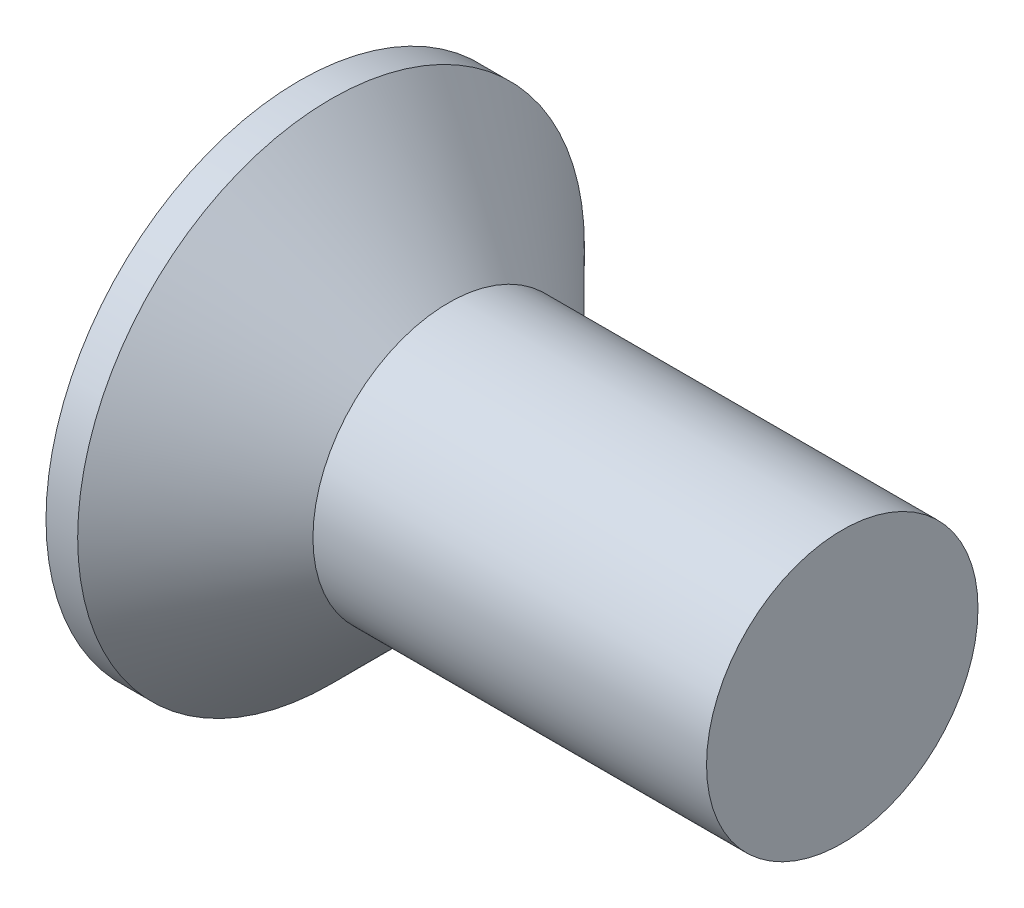
SolidWorks part; units mm, degrees
ref_plane "Plane1" through (0, 0, 0) normal (0, 0, 1) x (1, 0, 0)
ref_plane "Plane2" through (0, 0, 0) normal (0, 1, 0) x (1, 0, 0)
ref_plane "Plane3" through (0, 0, 0) normal (1, 0, 0) x (0, 0, -1)
sketch "BodySke" plane through (0, 0, 0) normal (0, 0, 1) x (1, 0, 0)
  line L0 (0, 0) -> (0, 2.8)
  line L1 (0, 2.8) -> (0.35, 2.8)
  line L2 (1.65, 1.5) -> (6, 1.5)
  line L3 (6, 1.5) -> (6, 0)
  line L4 (6, 0) -> (0, 0)
  line L5 (-6.35, 0) -> (82.55, 0) construction
  line L6 (1.65, -1.5) -> (6, -1.5) construction
  line L7 (0.35, -2.8) -> (1.65, -1.5) construction
  line L8 (0.35, 2.8) -> (1.65, 1.5)
  line L9 (0, -2.8) -> (0.35, -2.8) construction
  line L10 (2.15, 3.0875) -> (2.15, -6.4375) construction
  line L11 (0, 6.35) -> (0, -3.175) construction
  dimension "Diameter" = 3
  dimension "Length" = 6
  dimension "Head_ht" = 1.65
  dimension "Head_dia" = 5.6
  dimension "Head_ang" = 90
  dimension "D6" = 0.35
  dimension "Advance" = 0.5
  dimension "Thread_nom" = 6
revolve "Base-Revolve" add sketch "BodySke" angle 360 about L5
cosmetic thread "ThreadCosmetic" parameters "Thread_length"=3.85, "Thread_minor"=2.459
sketch "Sketch3" plane through (0, 0, 0) normal (-1, 0, 0) x (0, 0, 1)
  line L0 (-0.265, 1.4) -> (0.265, 1.4)
  line L1 (0.265, 1.4) -> (0.265, -1.4)
  line L2 (0.265, -1.4) -> (-0.265, -1.4)
  line L3 (-0.265, -1.4) -> (-0.265, 1.4)
  dimension "Cross_dia" = 2.8
  dimension "Cross_width" = 0.53
  dimension "D1" = 1.4
  dimension "D2" = 0.265
ref_plane "Plane4" through (1.5, 0, 0) normal (-1, 0, 0) x (0, 0, 1)
sketch "Sketch4" plane through (1.5, 0, 0) normal (-1, 0, 0) x (0, 0, 1)
  line L0 (-0.265, 0.6521) -> (0.265, 0.6521)
  line L3 (0.265, 0.6521) -> (0.265, -0.6521)
  line L4 (0.265, -0.6521) -> (-0.265, -0.6521)
  line L5 (-0.265, -0.6521) -> (-0.265, 0.6521)
  dimension "D2" = 1.3043
  dimension "D1" = 0.53
  dimension "D4" = 0.6521
  dimension "D3" = 0.265
loft "Recess" cut profiles "Sketch3", "Sketch4"
pattern_circular "RecPat" count 2 every 90 about axis through (0, 0, 0) along (1, 0, 0) of "Recess"
sketch "RecCorSke" plane through (0, 0, 0) normal (0, 0, 1) x (1, 0, 0)
  line L0 (-3.175, 0) -> (15.875, 0) construction
  line L2 (0, 0) -> (0, 0.6609)
  line L3 (0, 0.6609) -> (1.5, 0.556)
  line L4 (1.5, 0.556) -> (1.6807, 0)
  line L5 (1.6807, 0) -> (0, 0)
  dimension "Diameter" = 1.112
  dimension "Depth" = 1.5
  dimension "Draft_angle" = 4
  dimension "Bottom_angle" = 18
revolve "RecessCore" cut sketch "RecCorSke" angle 360 about L0
sketch "Sketch5" plane through (0, 4.1645, -0.7173) normal (-1, 0, 0) x (0, 0, 1)
  line L0 (0.7173, -4.1645) -> (0.7173, 12.7) construction
  line L1 (1.1673, -1.4009) -> (1.1673, -6.9281)
  line L3 (0.2673, -6.9281) -> (0.2673, -1.4009)
  arc A0 (1.1673, -1.4009) -> (0.2673, -1.4009) centre (0.7173, -4.1645) ccw
  circle A1 centre (0.7173, -4.1645) radius 2.8 construction
  arc A2 (0.2673, -6.9281) -> (1.1673, -6.9281) centre (0.7173, -4.1645) ccw
  dimension "Slot_width" = 0.9
extrude "Slot" [suppressed] cut sketch "Sketch5" against normal blind 0.7
equation "\"D1@Sketch3\" = \"Cross_dia@Sketch3\" / 2"
equation "\"D2@Sketch3\" = \"Cross_width@Sketch3\" / 2"
equation "\"Depth@RecCorSke\" = \"Cross_depth@Plane4\""
equation "\"D1@Sketch4\" = \"Cross_width@Sketch3\""
equation "\"D2@Sketch4\" = \"Cross_dia@Sketch3\" - 2.0 * \"Cross_depth@Plane4\" * tan(26.5  * 0.017453292)"
equation "\"D3@Sketch4\" = \"D1@Sketch4\" / 2"
equation "\"D4@Sketch4\" = \"D2@Sketch4\" / 2"
equation "\"Thread_length@ThreadCosmetic\" = ((sgn( (\"Length@BodySke\" - \"Advance@BodySke\" * 1.0 - \"Head_ht@BodySke\" ) - \"Thread_nom@BodySke\" )-1)*( (\"Length@BodySke\" - \"Advance@BodySke\" * 1.0 - \"Head_ht@BodySke\" ) - \"Thread_nom@BodySke\" ))/-2+ \"Thread_nom@BodySke\""
